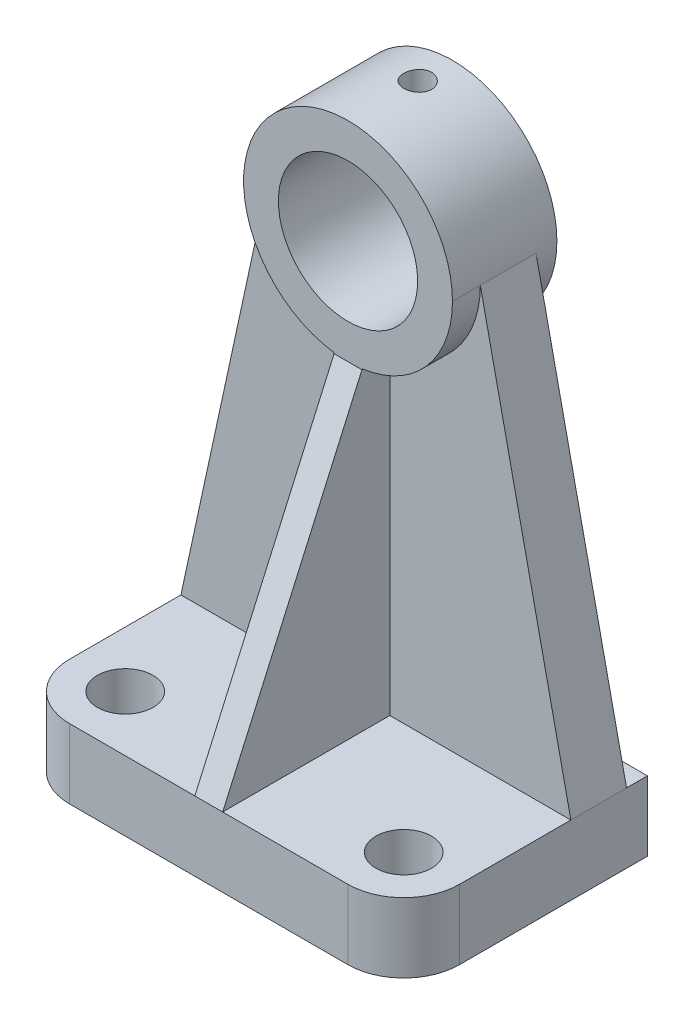
SolidWorks part; units mm, degrees
ref_plane "Ön Düzlem" through (0, 0, 0) normal (0, 0, 1) x (1, 0, 0)
ref_plane "Üst Düzlem" through (0, 0, 0) normal (0, 1, 0) x (1, 0, 0)
ref_plane "Sağ Düzlem" through (0, 0, 0) normal (1, 0, 0) x (0, 0, -1)
sketch "Çizim1" plane through (0, 0, 0) normal (0, 1, 0) x (1, 0, 0)
  line L1 (0, 0) -> (560, 0)
  line L2 (0, 0) -> (0, -270)
  line L3 (80, -350) -> (480, -350)
  line L4 (560, 0) -> (560, -270)
  arc A0 (480, -350) -> (560, -270) centre (480, -270) ccw
  arc A1 (0, -270) -> (80, -350) centre (80, -270) ccw
  circle A2 centre (80, -270) radius 40
  circle A3 centre (480, -270) radius 40
  point P9 (0, -350)
  dimension "D3" = 80
  dimension "D4" = 80
  dimension "D5" = 80
  dimension "D1" = 560
  dimension "D2" = 350
extrude "Yükseklik-Ekstrüzyon1" add sketch "Çizim1" along normal blind 100
sketch "Çizim2" plane through (0, 0, 0) normal (0, 0, 1) x (1, 0, 0)
  line L0 (80, 0) -> (480, 0) construction
  line L1 (280, 0) -> (280, 478.2484) construction
  circle A0 centre (280, 700) radius 150
  circle A1 centre (280, 700) radius 100
  point P7 (0, 0)
  dimension "D1" = 300
  dimension "D2" = 200
  dimension "D3" = 700
extrude "Yükseklik-Ekstrüzyon2" add sketch "Çizim2" along normal blind 150 separate body
ref_plane "Düzlem1" through (0, 0, 30) normal (0, 0, 1) x (1, 0, 0)
sketch "Çizim5" plane through (0, 0, 30) normal (0, 0, 1) x (1, 0, 0)
  line L0 (130, 700) -> (0, 100)
  line L1 (0, 100) -> (560, 100)
  line L2 (560, 100) -> (430, 700)
  circle A0 centre (280, 700) radius 150 construction
  arc A1 (130, 700) -> (430, 700) centre (280, 700) ccw
  point P6 (0, 0)
  point P10 (0, 0)
extrude "Yükseklik-Ekstrüzyon3" add sketch "Çizim5" along normal blind 80
ref_plane "Düzlem2" through (0, 650, 0) normal (0, 1, 0) x (1, 0, 0)
sketch "Çizim6" plane through (0, 650, 0) normal (0, 1, 0) x (1, 0, 0)
  line L0 (380, 0) -> (180, 0) construction
  line L1 (280, 0) -> (280, -50) construction
  line L2 (430, 0) -> (130, 0) construction
  circle A0 centre (280, -50) radius 20
  point P5 (0, 0)
  point P8 (0, 0)
  dimension "D1" = 40
  dimension "D2" = 50
extrude "Kes-Ekstrüzyon1" cut sketch "Çizim6" along normal through all
ref_plane "Düzlem3" through (280, 0, 0) normal (1, 0, 0) x (0, 0, -1)
sketch "Çizim7" plane through (280, 0, 0) normal (1, 0, 0) x (0, 0, -1)
  line L0 (-150, 550) -> (-110, 550)
  line L1 (-110, 550) -> (-110, 100)
  line L2 (-110, 100) -> (-350, 100)
  line L3 (-350, 100) -> (-150, 550)
extrude "Yükseklik-Ekstrüzyon11" add sketch "Çizim7" along normal mid plane 40 separate body contours L3 L2 L1 L0
sketch "Çizim8" plane through (0, 550, 0) normal (0, 1, 0) x (1, 0, 0)
  line L4 (260, -110) -> (260, -150)
  line L5 (260, -150) -> (300, -150)
  line L6 (300, -150) -> (300, -110)
  line L7 (300, -110) -> (260, -110)
  line L8 (260, -110) -> (260, -150)
  line L9 (260, -150) -> (300, -150)
  line L10 (300, -150) -> (300, -110)
  line L11 (300, -110) -> (260, -110)
  dimension "D1" = 0
extrude "Yükseklik-Ekstrüzyon12" add sketch "Çizim8" along normal up to surface (52.0204 mm away)
